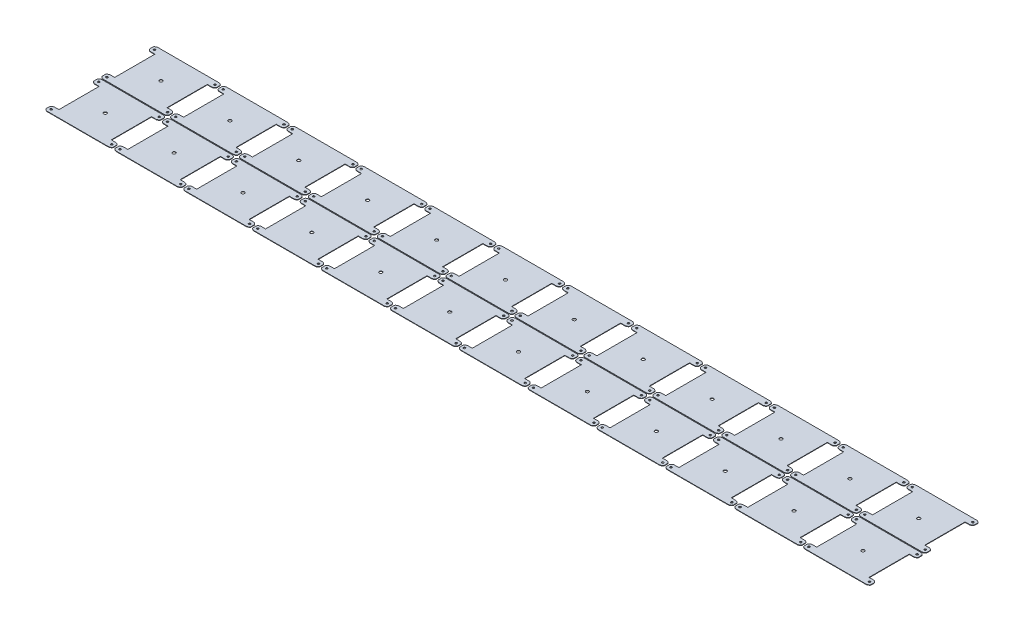
SolidWorks part; units mm, degrees
ref_plane "Front Plane" through (0, 0, 0) normal (0, 0, 1) x (1, 0, 0)
ref_plane "Top Plane" through (0, 0, 0) normal (0, 1, 0) x (1, 0, 0)
ref_plane "Right Plane" through (0, 0, 0) normal (1, 0, 0) x (0, 0, -1)
sketch "Sketch1" plane through (0, 0, 0) normal (0, 1, 0) x (1, 0, 0)
  line L5 (-62.5, 56.5) -> (62.5, 56.5)
  line L41 (0, 41.5) -> (0, 0) construction
  line L42 (-62.5, 41.5) -> (62.5, 41.5) construction
  line L43 (-62.5, -56.5) -> (62.5, -56.5)
  line L44 (-62.5, 49) -> (62.5, 49) construction
  line L45 (-62.5, 56.5) -> (-62.5, 41.5) construction
  line L46 (0, 41.5) -> (0, 49) construction
  line L47 (-62.5, -49) -> (62.5, -49) construction
  line L48 (62.5, 56.5) -> (62.5, 41.5) construction
  line L49 (0, -41.5) -> (0, 0) construction
  line L50 (-62.5, -56.5) -> (-62.5, -41.5) construction
  line L51 (-62.5, -41.5) -> (-54, -41.5)
  line L52 (62.5, -56.5) -> (62.5, -41.5) construction
  line L58 (-54, 41.5) -> (-62.5, 41.5)
  line L66 (-54, 41.5) -> (-54, -41.5)
  line L71 (-54, 0) -> (0, 0) construction
  line L72 (54, 41.5) -> (54, -41.5)
  line L73 (-62.5, -41.5) -> (62.5, -41.5) construction
  line L74 (0, -49) -> (0, -41.5) construction
  line L75 (62.5, 41.5) -> (54, 41.5)
  line L76 (62.5, -41.5) -> (54, -41.5)
  circle A1 centre (-62.5, 49) radius 2
  circle A2 centre (62.5, 49) radius 2
  circle A3 centre (62.5, -49) radius 2
  circle A4 centre (-62.5, -49) radius 2
  arc A5 (-62.5, 56.5) -> (-62.5, 41.5) centre (-62.5, 49) ccw
  arc A6 (-62.5, -41.5) -> (-62.5, -56.5) centre (-62.5, -49) ccw
  arc A7 (62.5, -56.5) -> (62.5, -41.5) centre (62.5, -49) ccw
  arc A8 (62.5, 41.5) -> (62.5, 56.5) centre (62.5, 49) ccw
  circle A13 centre (0, 0) radius 3.175
  dimension "D1" = 83
  dimension "D2" = 4
  dimension "D4" = 8.5
  dimension "D14" = 6.35
  dimension "D3" = 125
  dimension "D10" = 15
extrude "Boss-Extrude1" add sketch "Sketch1" along normal blind 0.86
sketch "Sketch2" plane through (0, 0, 0) normal (0, 1, 0) x (1, 0, 0)
  line L0 (62.5, 56.5) -> (-62.5, 56.5) construction
  line L1 (-69, 57.5) -> (69, 57.5)
  line L2 (-69, 57.5) -> (-69, -57.5)
  line L3 (-69, -57.5) -> (69, -57.5)
  line L4 (69, 57.5) -> (69, -57.5)
  line L5 (-69, 57.5) -> (69, -57.5) construction
  line L6 (-69, -57.5) -> (69, 57.5) construction
  line L8 (-71, 58.5) -> (71, 58.5)
  line L9 (-71, 58.5) -> (-71, -58.5)
  line L10 (-71, -58.5) -> (71, -58.5)
  line L11 (71, 58.5) -> (71, -58.5)
  line L12 (-71, 58.5) -> (71, -58.5) construction
  line L13 (-71, -58.5) -> (71, 58.5) construction
  arc A0 (-62.5, -41.5) -> (-62.5, -56.5) centre (-62.5, -49) ccw construction
  point P0 (0, 0)
  point P11 (0, 0)
  dimension "D1" = 1
  dimension "D2" = 6.5
  dimension "D3" = 2
  dimension "D4" = 1
extrude "Cut-Extrude1" cut sketch "Sketch2" against normal blind 10 and the other way blind 10
pattern_linear "LPattern2" count 2 spacing 115 along (0, 0, -1) count 12 spacing 142 along (1, 0, 0) of bodies 116 101
